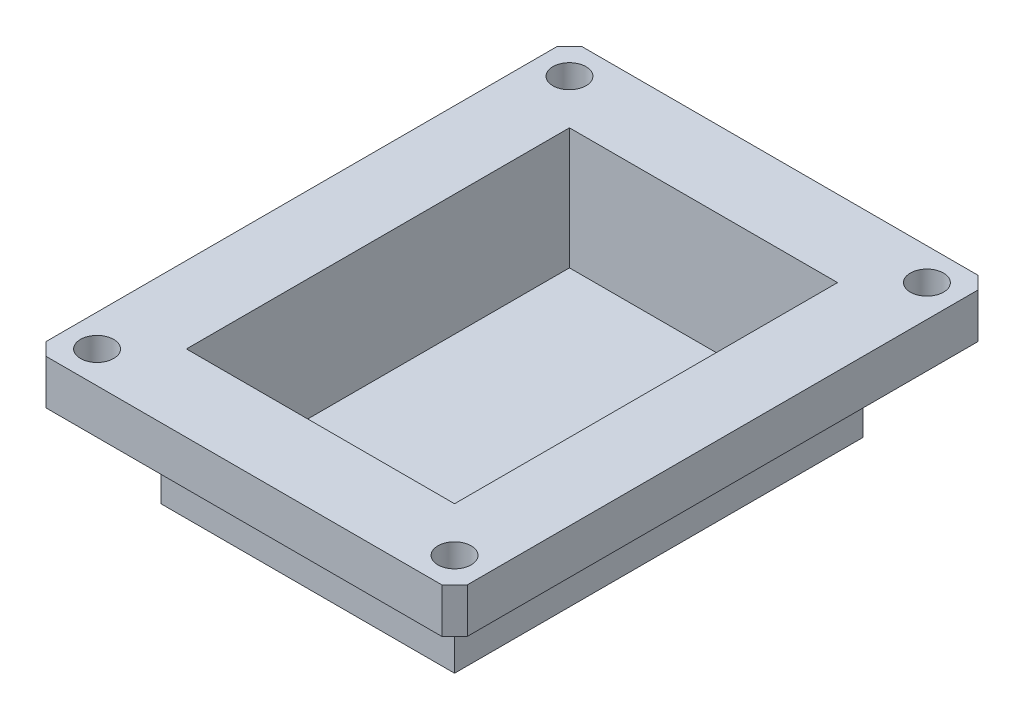
SolidWorks part; units mm, degrees
ref_plane "Front Plane" through (0, 0, 0) normal (0, 0, 1) x (1, 0, 0)
ref_plane "Top Plane" through (0, 0, 0) normal (0, 1, 0) x (1, 0, 0)
ref_plane "Right Plane" through (0, 0, 0) normal (1, 0, 0) x (0, 0, -1)
sketch "Sketch1" plane through (0, 0, 0) normal (0, 1, 0) x (1, 0, 0)
  line L1 (-52.5, -114.8422) -> (52.5, -114.8422)
  line L2 (-52.5, -114.8422) -> (-52.5, 35.1578)
  line L3 (-52.5, 35.1578) -> (52.5, 35.1578)
  line L4 (52.5, -114.8422) -> (52.5, 35.1578)
  line L5 (-52.5, -114.8422) -> (52.5, 35.1578) construction
  line L6 (-52.5, 35.1578) -> (52.5, -114.8422) construction
  line L7 (-52.5, 35.1578) -> (-57.5, 35.1578)
  line L8 (-52.5, 35.1578) -> (-52.5, 40.1578)
  line L9 (-52.5, 40.1578) -> (-57.5, 40.1578)
  line L10 (-57.5, 35.1578) -> (-57.5, 40.1578)
  line L11 (52.5, -114.8422) -> (57.5, -114.8422)
  line L12 (52.5, -114.8422) -> (52.5, -119.8422)
  line L13 (52.5, -119.8422) -> (57.5, -119.8422)
  line L14 (57.5, -114.8422) -> (57.5, -119.8422)
  line L15 (-57.5, 40.1578) -> (57.5, 40.1578)
  line L16 (-57.5, 40.1578) -> (-57.5, -119.8422)
  line L17 (-57.5, -119.8422) -> (57.5, -119.8422)
  line L18 (57.5, 40.1578) -> (57.5, -119.8422)
  point P0 (0, 0)
  point P11 (0, 0)
  point P14 (0, 0)
  point P15 (0, 0)
  dimension "D1" = 105
  dimension "D2" = 150
  dimension "D3" = 5
  dimension "D4" = 90
  dimension "D5" = 90
  dimension "D6" = 5
  dimension "D7" = 90
  dimension "D8" = 5
  dimension "D9" = 5
extrude "Boss-Extrude1" add sketch "Sketch1" along normal blind 35 contours L16 L17 L12 L1 L2 L7 | L1 L4 L3 L2 | L18 L15 L8 L3 L4 L11 | L14 L11 L12 L13 | L10 L7 L8 L9
sketch "Sketch2" plane through (0, 35, 0) normal (0, 1, 0) x (1, 0, 0)
  line L5 (-52.5, 35.1578) -> (52.5, 35.1578)
  line L6 (-52.5, 35.1578) -> (-52.5, -114.8422)
  line L7 (-52.5, -114.8422) -> (52.5, -114.8422)
  line L8 (52.5, 35.1578) -> (52.5, -114.8422)
  line L9 (-52.5, 35.1578) -> (-77.5, 35.1578)
  line L10 (-52.5, 35.1578) -> (-52.5, 60.1578)
  line L11 (-52.5, 60.1578) -> (-77.5, 60.1578)
  line L12 (-77.5, 35.1578) -> (-77.5, 60.1578)
  line L13 (52.5, -114.8422) -> (77.5, -114.8422)
  line L14 (52.5, -114.8422) -> (52.5, -139.8422)
  line L15 (52.5, -139.8422) -> (77.5, -139.8422)
  line L16 (77.5, -114.8422) -> (77.5, -139.8422)
  line L17 (-77.5, 60.1578) -> (77.5, 60.1578)
  line L18 (-77.5, 60.1578) -> (-77.5, -139.8422)
  line L19 (-77.5, -139.8422) -> (77.5, -139.8422)
  line L20 (77.5, 60.1578) -> (77.5, -139.8422)
  line L21 (-77.5, 60.1578) -> (-82.5, 60.1578)
  line L22 (-77.5, 60.1578) -> (-77.5, 65.1578)
  line L23 (-77.5, 65.1578) -> (-82.5, 65.1578)
  line L24 (-82.5, 60.1578) -> (-82.5, 65.1578)
  line L25 (77.5, -139.8422) -> (82.5, -139.8422)
  line L26 (77.5, -139.8422) -> (77.5, -144.8422)
  line L27 (77.5, -144.8422) -> (82.5, -144.8422)
  line L28 (82.5, -139.8422) -> (82.5, -144.8422)
  line L29 (-82.5, 65.1578) -> (82.5, 65.1578)
  line L30 (-82.5, 65.1578) -> (-82.5, -144.8422)
  line L31 (-82.5, -144.8422) -> (82.5, -144.8422)
  line L32 (82.5, 65.1578) -> (82.5, -144.8422)
  line M25 (57.5, -119.8422) -> (57.5, 40.1578)
  line M26 (57.5, 40.1578) -> (-57.5, 40.1578)
  line M27 (-57.5, 40.1578) -> (-57.5, -119.8422)
  line M28 (-57.5, -119.8422) -> (57.5, -119.8422)
  dimension "D1" = 90
  dimension "D2" = 90
  dimension "D3" = 25
  dimension "D4" = 25
  dimension "D5" = 25
  dimension "D6" = 25
  dimension "D7" = 90
  dimension "D8" = 90
  dimension "D9" = 90
  dimension "D10" = 90
  dimension "D11" = 90
  dimension "D12" = 25
  dimension "D13" = 5
  dimension "D14" = 5
  dimension "D15" = 90
  dimension "D16" = 90
  dimension "D17" = 90
  dimension "D18" = 90
  dimension "D19" = 90
  dimension "D20" = 5
  dimension "D21" = 5
  dimension "D22" = 90
  dimension "D23" = 90
  dimension "D24" = 90
extrude "Boss-Extrude2" add sketch "Sketch2" along normal blind 17.5 contours L30 L31 L26 L15 L19 L18 L12 L21 | L32 L29 L22 L11 L17 L20 L16 L25 | L24 L21 L22 L23 | L12 L9 L10 L11 M27 M26 | L20 L17 L10 L13 M26 M25 | L8 L13 L10 L5 M25 M26 | L9 L10 M26 M27 | L14 L7 L6 L9 M27 M28 | L18 L19 L14 L9 M28 M27 | L8 L5 L6 L7 | L13 L14 M28 M25 | L16 L13 L14 L15 M25 M28 | L28 L25 L26 L27
sketch "Sketch3" plane through (0, 52.5, 0) normal (0, 1, 0) x (1, 0, 0)
  line L1 (-52.5, 35.1578) -> (52.5, 35.1578)
  line L2 (-52.5, 35.1578) -> (-52.5, -114.8422)
  line L3 (-52.5, -114.8422) -> (52.5, -114.8422)
  line L4 (52.5, 35.1578) -> (52.5, -114.8422)
extrude "Cut-Extrude1" cut sketch "Sketch3" against normal blind 47.5
sketch "Sketch4" plane through (0, 52.5, 0) normal (0, 1, 0) x (1, 0, 0)
  line L0 (-82.5, 65.1578) -> (-57.5, 40.1578) construction
  line L1 (-57.5, 40.1578) -> (-57.5, -39.8422) construction
  line L2 (-57.5, -39.8422) -> (-82.5, -39.8422) construction
  line L3 (-82.5, -39.8422) -> (0, -114.8422) construction
  line L4 (0, -114.8422) -> (0, -144.8422) construction
  circle A0 centre (-70, 52.6578) radius 6.5
  circle A1 centre (-70, -132.3422) radius 6.5
  circle A2 centre (70, -132.3422) radius 6.5
  circle A3 centre (70, 52.6578) radius 6.5
extrude "Cut-Extrude2" cut sketch "Sketch4" against normal up to next
chamfer "Chamfer1" distance 5 angle 45 4 edges at (0, 35, 119.8422) (-57.5, 35, 39.8422) (0, 35, -40.1578) (57.5, 35, 39.8422)
chamfer "Chamfer2" distance 5 angle 45 4 edges at (82.5, 43.75, 144.8422) (82.5, 43.75, -65.1578) (-82.5, 43.75, -65.1578) (-82.5, 43.75, 144.8422)
sketch "Sketch7" plane through (0, 52.5, 0) normal (0, 1, 0) x (1, 0, 0)
  line L1 (-52.5, 35.1578) -> (52.5, 35.1578)
  line L2 (-52.5, 35.1578) -> (-52.5, -114.8422)
  line L3 (-52.5, -114.8422) -> (52.5, -114.8422)
  line L4 (52.5, 35.1578) -> (52.5, -114.8422)
  line L7 (-70, 52.6578) -> (70, 52.6578)
  line L8 (-70, 52.6578) -> (-70, -132.3422)
  line L9 (-70, -132.3422) -> (70, -132.3422)
  line L10 (70, 52.6578) -> (70, -132.3422)
